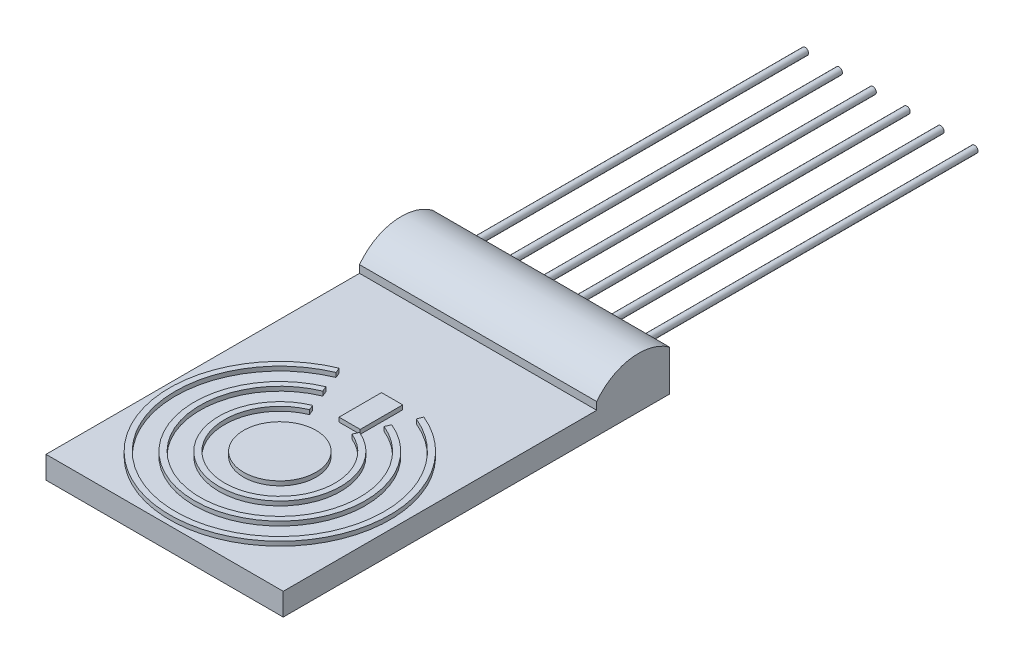
SolidWorks part; units mm, degrees
ref_plane "Front Plane" through (0, 0, 0) normal (0, 0, 1) x (1, 0, 0)
ref_plane "Top Plane" through (0, 0, 0) normal (0, 1, 0) x (1, 0, 0)
ref_plane "Right Plane" through (0, 0, 0) normal (1, 0, 0) x (0, 0, -1)
sketch "Sketch1" plane through (0, 0, 0) normal (0, 1, 0) x (1, 0, 0)
  line L0 (0, 0) -> (0, 11.4) construction
  line L2 (-3.5, 11.4) -> (3.5, 11.4)
  line L3 (-3.5, 11.4) -> (-3.5, 0)
  line L4 (-3.5, 0) -> (3.5, 0)
  line L5 (3.5, 11.4) -> (3.5, 0)
  point P8 (0, 0)
  dimension "D1" = 7
  dimension "D2" = 11.4
extrude "Boss-Extrude1" add sketch "Sketch1" along normal blind 0.6604
sketch "Sketch3" plane through (-3.5, 0, 0) normal (-1, 0, 0) x (0, 0, 1)
  line L0 (-11.4, 0.6604) -> (-11.4, 1.2)
  line L2 (-11.4, 0) -> (0, 0) construction
  line L4 (-10.485, 1.5) -> (-9.9152, 1.5) construction
  line L5 (-9.25, 0.6604) -> (-9.25, 0.8837)
  line L6 (-11.4, 0.6604) -> (0, 0.6604) construction
  line L7 (-11.4, 0.6604) -> (-11.4, 0) construction
  line L8 (-11.4, 0.6604) -> (-9.25, 0.6604)
  arc A0 (-11.4, 1.2) -> (-9.25, 0.8837) centre (-10.485, -0.0455) cw
  point P5 (-10.485, 1.5)
  dimension "D1" = 1.5
  dimension "D2" = 2.15
  dimension "D3" = 1.2
extrude "Boss-Extrude2" add sketch "Sketch3" against normal up to surface (7 mm away) up to face at (3.5, 0.3302, -5.7)
sketch "Sketch4" plane through (0, 0.6604, 0) normal (0, 1, 0) x (1, 0, 0)
  line L0 (0, 0) -> (0, 9.25) construction
  line L1 (3.5, 9.25) -> (-3.5, 9.25) construction
  line L2 (-3.25, 3.4) -> (-3.08, 3.4) construction
  line L3 (-3.08, 3.4) -> (-2.5233, 3.4) construction
  line L4 (-2.5233, 3.4) -> (-2.3533, 3.4) construction
  line L5 (-2.3533, 3.4) -> (-1.7967, 3.4) construction
  line L6 (-1.7967, 3.4) -> (-1.6267, 3.4) construction
  line L7 (-1.6267, 3.4) -> (-1.07, 3.4) construction
  line L8 (0, 3.4) -> (0.4115, 4.3877) construction
  line L9 (0, 6.4) -> (0.6256, 6.4)
  line L10 (0, 6.4) -> (0, 5.1459)
  line L11 (0, 5.1459) -> (0.6256, 5.1459)
  line L12 (0.6256, 6.4) -> (0.6256, 5.1459)
  line L13 (0, 3.4) -> (-0.4115, 4.3877) construction
  line L14 (-0.6256, 4.9015) -> (-0.691, 5.0585)
  line L15 (0.6256, 4.9015) -> (0.691, 5.0585)
  line L16 (0.9051, 5.5723) -> (0.9705, 5.7292)
  line L17 (1.1846, 6.2431) -> (1.25, 6.4)
  line L18 (-0.9051, 5.5723) -> (-0.9705, 5.7292)
  line L19 (-1.1846, 6.2431) -> (-1.25, 6.4)
  line L20 (3.5, 11.4) -> (-3.5, 11.4) construction
  circle A0 centre (0, 3.4) radius 1.07
  arc A1 (-0.6256, 4.9015) -> (0.6256, 4.9015) centre (0, 3.4) ccw
  arc A2 (-0.691, 5.0585) -> (0.691, 5.0585) centre (0, 3.4) ccw
  arc A3 (-0.9051, 5.5723) -> (0.9051, 5.5723) centre (0, 3.4) ccw
  arc A4 (-0.9705, 5.7292) -> (0.9705, 5.7292) centre (0, 3.4) ccw
  arc A5 (-1.25, 6.4) -> (1.25, 6.4) centre (0, 3.4) ccw
  arc A6 (-1.1846, 6.2431) -> (1.1846, 6.2431) centre (0, 3.4) ccw
  dimension "D3" = 2.14
  dimension "D1" = 0.17
  dimension "D2" = 3.25
  dimension "D4" = 2.5
  dimension "D5" = 1.25
  dimension "D6" = 5
extrude "Boss-Extrude3" add sketch "Sketch4" along normal blind 0.127
sketch "Sketch5" plane through (0, 0, -11.4) normal (0, 0, -1) x (-1, 0, 0)
  line L0 (-2.5, 0.7604) -> (-1.5, 0.7604) construction
  line L1 (-1.5, 0.7604) -> (-0.5, 0.7604) construction
  line L2 (-0.5, 0.7604) -> (0.5, 0.7604) construction
  line L3 (0.5, 0.7604) -> (1.5, 0.7604) construction
  line L4 (1.5, 0.7604) -> (2.5, 0.7604) construction
  line L5 (-3.5, 0.6604) -> (3.5, 0.6604) construction
  line L6 (0, 0) -> (0, 0.7604) construction
  line L7 (-3.5, 1.2) -> (-3.5, 0) construction
  circle A0 centre (-2.5, 0.7604) radius 0.1
  circle A1 centre (-1.5, 0.7604) radius 0.1
  circle A2 centre (-0.5, 0.7604) radius 0.1
  circle A3 centre (0.5, 0.7604) radius 0.1
  circle A4 centre (1.5, 0.7604) radius 0.1
  circle A5 centre (2.5, 0.7604) radius 0.1
  point P14 (-2.4, 0.7604)
  point P15 (-1.6, 0.7604)
  point P16 (-0.4, 0.7604)
  point P17 (0.4, 0.7604)
  dimension "D1" = 0.2
  dimension "D2" = 0.8
  dimension "D3" = 1
  dimension "D4" = 1
extrude "Boss-Extrude4" add sketch "Sketch5" along normal blind 10
